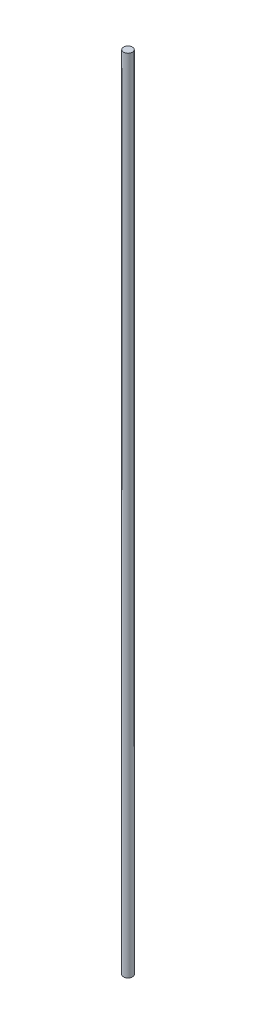
SolidWorks part; units mm, degrees
material "Custom Plastic"
ref_plane "Front Plane" through (0, 0, 0) normal (0, 0, 1) x (1, 0, 0)
ref_plane "Top Plane" through (0, 0, 0) normal (0, 1, 0) x (1, 0, 0)
ref_plane "Right Plane" through (0, 0, 0) normal (1, 0, 0) x (0, 0, -1)
sketch "Sketch1" plane through (0, 0, 0) normal (0, 1, 0) x (1, 0, 0)
  circle A0 centre (0, 0) radius 2
  dimension "D1" = 4
extrude "Boss-Extrude2" add sketch "Sketch1" along normal blind 360
cosmetic thread "Cosmetic Thread4" parameters "D2"=3.22
